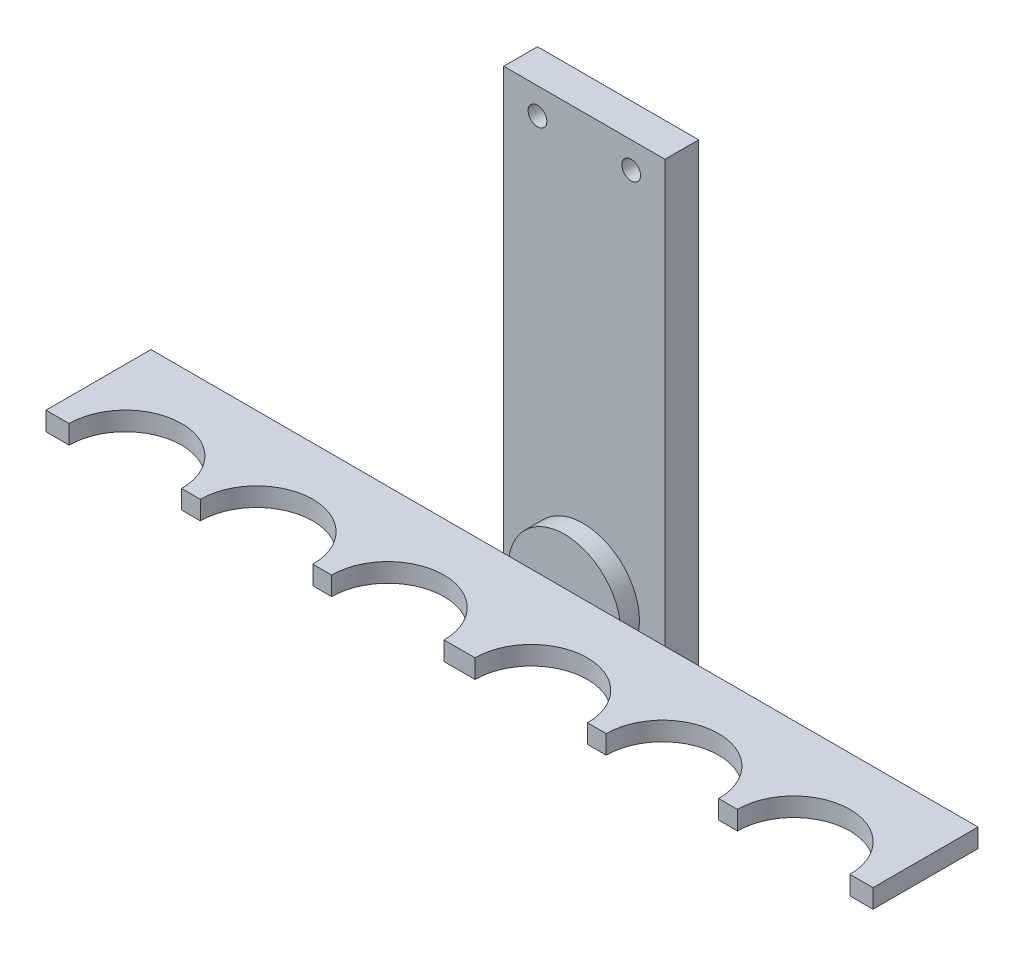
SolidWorks part; units mm, degrees
ref_plane "前视基准面" through (0, 0, 0) normal (0, 0, 1) x (1, 0, 0)
ref_plane "上视基准面" through (0, 0, 0) normal (0, 1, 0) x (1, 0, 0)
ref_plane "右视基准面" through (0, 0, 0) normal (1, 0, 0) x (0, 0, -1)
sketch "草图1" plane through (0, 0, 0) normal (0, 0, 1) x (1, 0, 0)
  line L0 (-21.2095, -9.4426) -> (-21.2095, -119.4426)
  line L1 (-21.2095, 5.5574) -> (21.7905, 5.5574)
  line L2 (-21.2095, 5.5574) -> (-21.2095, -9.4426)
  line L3 (-21.2095, -9.4426) -> (21.7905, -9.4426)
  line L4 (21.7905, 5.5574) -> (21.7905, -9.4426)
  line L5 (0.2905, -9.4426) -> (0.2905, 5.5574) construction
  line L6 (-21.2095, -119.4426) -> (21.7905, -119.4426)
  line L7 (21.7905, -119.4426) -> (21.7905, -9.4426)
  circle A0 centre (-12.2095, -1.4426) radius 2.5
  circle A1 centre (12.7905, -1.4426) radius 2.5
  dimension "D1" = 43
  dimension "D2" = 15
  dimension "D3" = 110
extrude "凸台-拉伸1" add sketch "草图1" along normal blind 9 contours L6 L7 L3 L0 | L5 L3 L4 L1 A1 | L3 L5 L1 L2 A0
sketch "草图2" plane through (0, 0, 0) normal (0, 0, -1) x (-1, 0, 0)
  line L0 (21.2095, -9.4426) -> (-21.7905, -9.4426) construction
  line L7 (21.2095, -9.4426) -> (-21.7905, -9.4426)
sketch "草图4" plane through (0, 0, 9) normal (0, 0, 1) x (1, 0, 0)
  line L0 (-21.2095, -119.4426) -> (21.7905, -119.4426) construction
  circle A0 centre (0, -104.4426) radius 15
  dimension "D1" = 30
extrude "凸台-拉伸2" add sketch "草图4" along normal blind 5
sketch "草图5" plane through (0, 0, 14) normal (0, 0, 1) x (1, 0, 0)
  line L0 (0, -106.9426) -> (0, -101.9426) construction
  line L1 (-110.301, -101.9426) -> (-110.301, -106.9426)
  line L2 (-110.301, -106.9426) -> (110.301, -106.9426)
  line L3 (-110.301, -101.9426) -> (110.301, -101.9426)
  line L4 (110.301, -101.9426) -> (110.301, -106.9426)
  line L5 (0, -104.4426) -> (0, -101.9426) construction
  dimension "D1" = 5
  dimension "D2" = 220.6019
extrude "凸台-拉伸3" add sketch "草图5" along normal blind 28
sketch "草图6" plane through (0, -106.9426, 0) normal (0, -1, 0) x (-1, 0, 0)
  line L0 (0, -42) -> (0, -14) construction
  line L1 (-110.301, -42) -> (110.301, -42) construction
  line L2 (14.7902, -14) -> (-14.7902, -14) construction
  circle A0 centre (-19.1277, -42) radius 15
  circle A1 centre (-54.1277, -42) radius 15
  circle A2 centre (-89.1277, -42) radius 15
  circle A3 centre (19.1277, -42) radius 15
  circle A4 centre (54.1277, -42) radius 15
  circle A5 centre (89.1277, -42) radius 15
  dimension "D1" = 3
  dimension "D2" = 30
  dimension "D3" = 38.2554
extrude "切除-拉伸1" cut sketch "草图6" against normal blind 28
